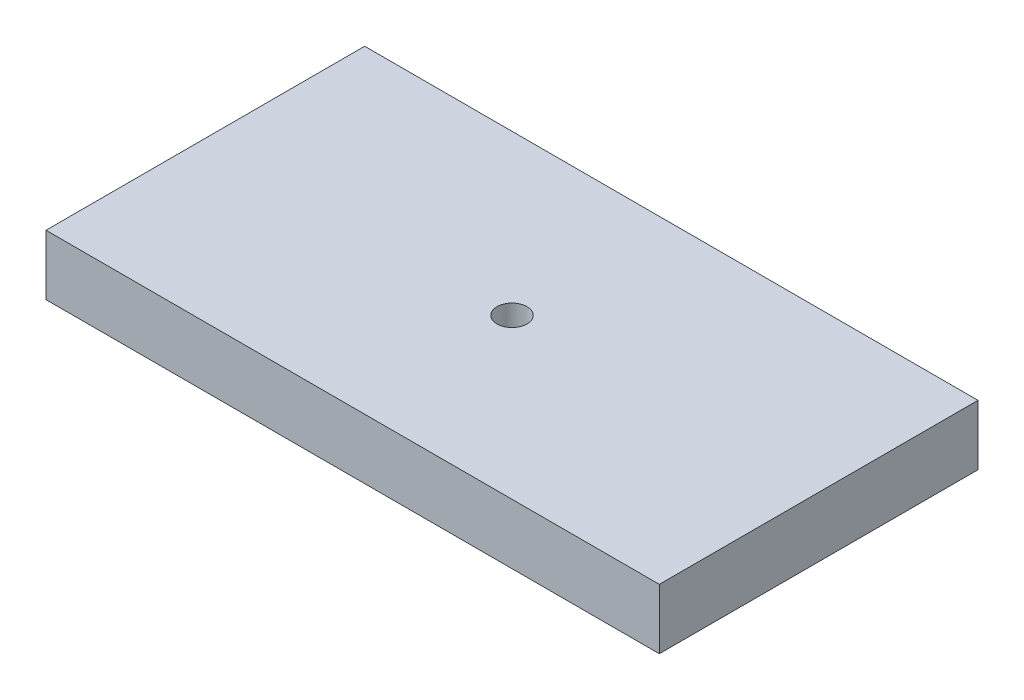
SolidWorks part; units mm, degrees
ref_plane "Front Plane" through (0, 0, 0) normal (0, 0, 1) x (1, 0, 0)
ref_plane "Top Plane" through (0, 0, 0) normal (0, 1, 0) x (1, 0, 0)
ref_plane "Right Plane" through (0, 0, 0) normal (1, 0, 0) x (0, 0, -1)
sketch "Sketch1" plane through (0, 0, 0) normal (0, 1, 0) x (1, 0, 0)
  line L1 (-51, 26.5) -> (51, 26.5)
  line L2 (-51, 26.5) -> (-51, -26.5)
  line L3 (-51, -26.5) -> (51, -26.5)
  line L4 (51, 26.5) -> (51, -26.5)
  line L5 (-51, 26.5) -> (51, -26.5) construction
  line L6 (-51, -26.5) -> (51, 26.5) construction
  point P0 (0, 0)
  dimension "D1" = 102
  dimension "D2" = 53
extrude "Boss-Extrude1" add sketch "Sketch1" along normal blind 10
sketch "Sketch2" plane through (0, 10, 0) normal (0, 1, 0) x (1, 0, 0)
  circle A0 centre (0, 0) radius 2.5
  dimension "D1" = 5
extrude "Cut-Extrude1" cut sketch "Sketch2" against normal blind 10
